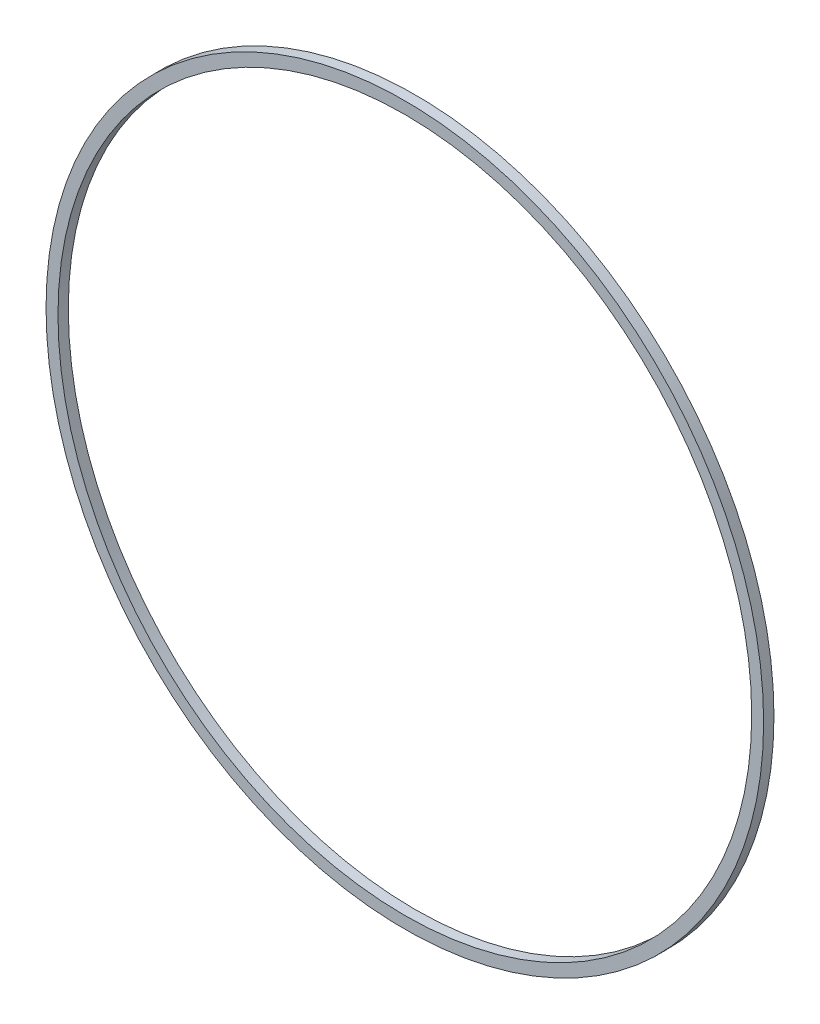
SolidWorks part; units mm, degrees
material "EPICHLOROHYDRIN"
ref_plane "Front Plane" through (0, 0, 0) normal (0, 0, 1) x (1, 0, 0)
ref_plane "Top Plane" through (0, 0, 0) normal (0, 1, 0) x (1, 0, 0)
ref_plane "Right Plane" through (0, 0, 0) normal (1, 0, 0) x (0, 0, -1)
sketch "Sketch2" plane through (0, 0, 0) normal (0, 0, 1) x (1, 0, 0)
  circle A0 centre (0, 0) radius 44.1325
  dimension "D1" = 88.265
extrude "Boss-Extrude1" add sketch "Sketch2" along normal blind 1.27
sketch "Sketch3" plane through (0, 0, 1.27) normal (0, 0, 1) x (1, 0, 0)
  circle A0 centre (0, 0) radius 42.6645
extrude "Cut-Extrude1" cut sketch "Sketch3" against normal blind 1.27
